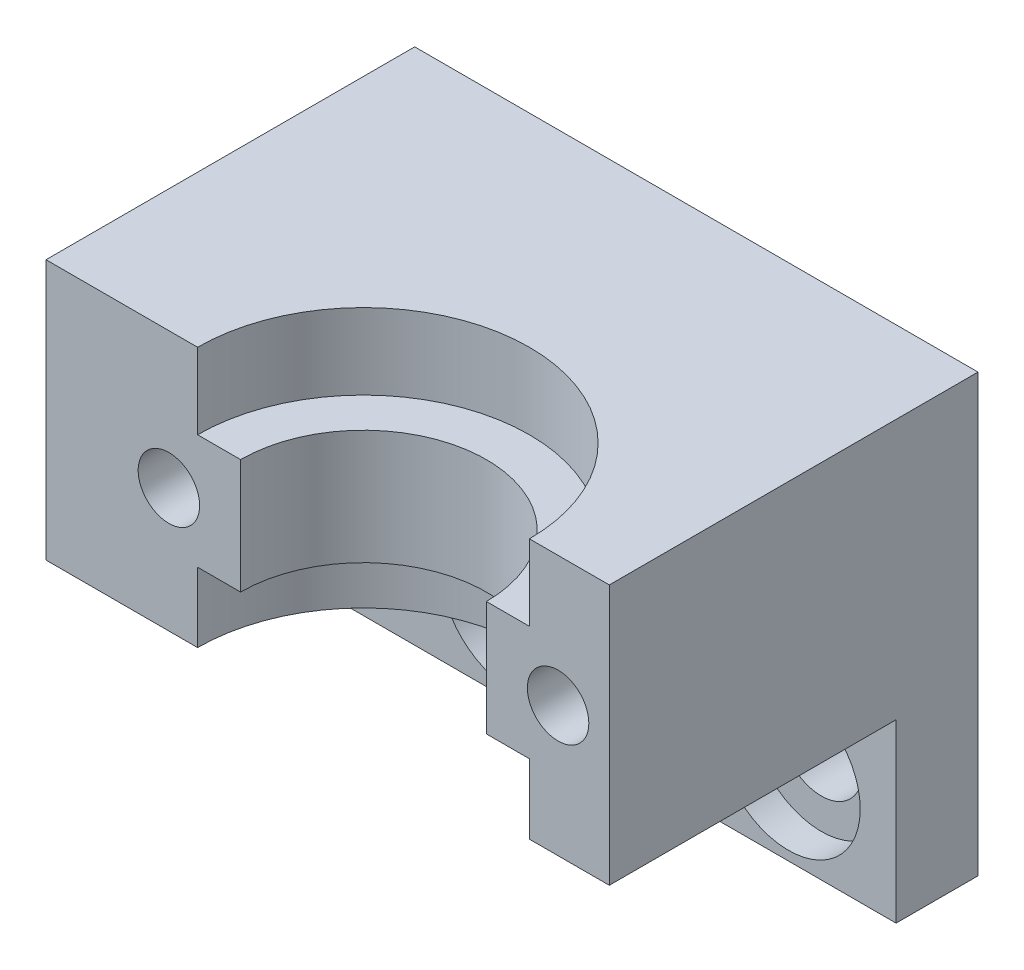
SolidWorks part; units mm, degrees
ref_plane "Front Plane" through (0, 0, 0) normal (0, 0, 1) x (1, 0, 0)
ref_plane "Top Plane" through (0, 0, 0) normal (0, 1, 0) x (1, 0, 0)
ref_plane "Right Plane" through (0, 0, 0) normal (1, 0, 0) x (0, 0, -1)
sketch "Sketch1" plane through (0, 0, 0) normal (0, 0, 1) x (1, 0, 0)
  line L1 (0, 0) -> (-24, 0)
  line L2 (0, 0) -> (0, 12.7)
  line L3 (0, 12.7) -> (-24, 12.7)
  line L4 (-24, 0) -> (-24, 12.7)
  circle A2 centre (-21.5, 6.05) radius 1.5
  circle A3 centre (-2.5, 6.35) radius 1.5
  dimension "D5" = 2.5
  dimension "D6" = 6.65
  dimension "D8" = 2.5
  dimension "D3" = 3
  dimension "D4" = 3
  dimension "D1" = 24
  dimension "D2" = 12.7
  dimension "D7" = 6.35
extrude "Boss-Extrude1" add sketch "Sketch1" along normal blind 18
sketch "Sketch3" plane through (0, 12.7, 0) normal (0, 1, 0) x (1, 0, 0)
  line L0 (0, 0) -> (0, -9) construction
  line L1 (0, -18) -> (0, 0) construction
  line L2 (0, -9) -> (-24, -9) construction
  line L3 (-24, -18) -> (-24, 0) construction
  line L4 (-12, -9) -> (-12, -18) construction
  line L5 (0, -18) -> (-24, -18) construction
  circle A0 centre (-12, -18) radius 6
  dimension "D1" = 12
extrude "Cut-Extrude1" cut sketch "Sketch3" against normal blind 15
sketch "Sketch4" plane through (0, 12.7, 0) normal (0, 1, 0) x (1, 0, 0)
  line L0 (0, -18) -> (0, 0) construction
  line L1 (0, 0) -> (-24, 0) construction
  circle A0 centre (-12, -18) radius 8.1
  dimension "D3" = 16.2
  dimension "D1" = 12
  dimension "D2" = 18
extrude "Cut-Extrude2" cut sketch "Sketch4" against normal blind 3.7
sketch "Sketch5" plane through (0, 0, 0) normal (0, -1, 0) x (1, 0, 0)
  circle A0 centre (-12, 18) radius 8.1 construction
  circle A1 centre (-12, 18) radius 8.1
extrude "Cut-Extrude3" cut sketch "Sketch5" against normal blind 3.4
sketch "Sketch6" plane through (0, 0, 0) normal (0, -1, 0) x (1, 0, 0)
  line L0 (-24, 0) -> (-24, 4)
  line L1 (-24, 18) -> (-24, 0) construction
  line L2 (-24, 4) -> (0, 4)
  line L3 (0, 18) -> (0, 0) construction
  line L4 (0, 4) -> (0, 0)
  line L5 (-24, 0) -> (0, 0) construction
  line L6 (0, 0) -> (-24, 0)
  dimension "D1" = 4
extrude "Boss-Extrude2" add sketch "Sketch6" along normal blind 8.6
sketch "Sketch7" plane through (0, 0, 4) normal (0, 0, 1) x (1, 0, 0)
  line L0 (-24, -8.6) -> (-24, 0) construction
  line L1 (0, -8.6) -> (-24, -8.6) construction
  line L2 (0, -8.6) -> (0, 0) construction
  circle A0 centre (-18.75, -4.65) radius 2
  circle A1 centre (-5.25, -4.65) radius 2
  dimension "D1" = 4
  dimension "D2" = 5.25
  dimension "D3" = 3.95
  dimension "D4" = 3.95
  dimension "D5" = 5.25
  dimension "D6" = 4
extrude "Cut-Extrude4" cut sketch "Sketch7" against normal blind 8.6
sketch "Sketch8" plane through (0, 0, 4) normal (0, 0, 1) x (1, 0, 0)
  line L0 (0, -8.6) -> (-24, -8.6) construction
  line L1 (-24, -8.6) -> (-24, 0) construction
  circle A0 centre (-18.75, -4.65) radius 3.5
  circle A1 centre (-5.25, -4.65) radius 3.5
  dimension "D2" = 5.25
  dimension "D3" = 7
  dimension "D4" = 13.5
  dimension "D5" = 3.95
  dimension "D6" = 7
  dimension "D1" = 3.95
extrude "Cut-Extrude5" cut sketch "Sketch8" against normal blind 1.6
sketch "Sketch9" plane through (-24, 0, 0) normal (-1, 0, 0) x (0, 0, 1)
  line L6 (0, 12.7) -> (0, -8.6)
  line L7 (0, -8.6) -> (4, -8.6)
  line L8 (4, -8.6) -> (4, 0)
  line L9 (4, 0) -> (18, 0)
  line L10 (18, 0) -> (18, 12.7)
  line L11 (18, 12.7) -> (0, 12.7)
  line L12 (0, 12.7) -> (0, -8.6)
  line L13 (0, -8.6) -> (4, -8.6)
  line L14 (4, -8.6) -> (4, 0)
  line L15 (4, 0) -> (18, 0)
  line L16 (18, 0) -> (18, 12.7)
  line L17 (18, 12.7) -> (0, 12.7)
  dimension "D1" = 0
extrude "Boss-Extrude3" add sketch "Sketch9" along normal blind 3.5
